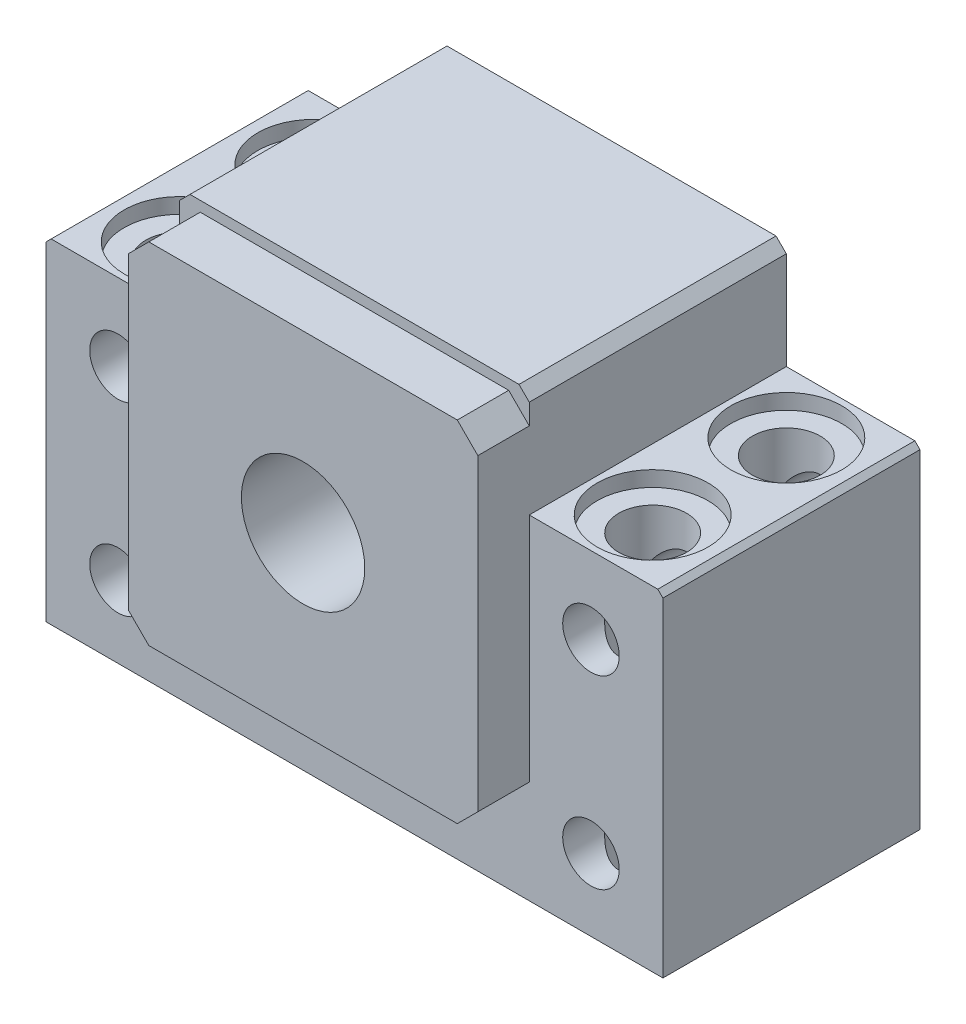
SolidWorks part; units mm, degrees
material "6061-T6 (SS)"
ref_plane "Спереди" through (0, 0, 0) normal (0, 0, 1) x (1, 0, 0)
ref_plane "Сверху" through (0, 0, 0) normal (0, 1, 0) x (1, 0, 0)
ref_plane "Справа" through (0, 0, 0) normal (1, 0, 0) x (0, 0, -1)
sketch "Эскиз1" plane through (0, 0, 0) normal (0, 0, 1) x (1, 0, 0)
  line L0 (0, -25) -> (0, 14) construction
  line L1 (-30, 7) -> (-30, -25)
  line L2 (-30, -25) -> (30, -25)
  line L3 (30, -25) -> (30, 7)
  line L4 (29.5, 7.5) -> (17, 7.5)
  line L5 (17, 7.5) -> (17, 17)
  line L6 (-17, 7.5) -> (-17, 17)
  line L7 (-29.5, 7.5) -> (-30, 7)
  line L8 (-29.5, 7.5) -> (-17, 7.5)
  line L9 (-23, -2.75) -> (-23, 2.75) construction
  line L10 (-16, 18) -> (16, 18)
  line L11 (23, -15.25) -> (23, -20.75) construction
  line L12 (-20.25, -18) -> (-25.75, -18) construction
  line L13 (20.25, -18) -> (25.75, -18) construction
  line L14 (-23, -15.25) -> (-23, -20.75) construction
  line L15 (23, -2.75) -> (23, 2.75) construction
  line L16 (30, 7) -> (29.5, 7.5)
  line L17 (-30, 0) -> (30, 0) construction
  line L18 (-17, 17) -> (-16, 18)
  line L19 (17, 17) -> (16, 18)
  circle A0 centre (0, 0) radius 6
  circle A1 centre (-23, 0) radius 2.75
  circle A2 centre (-23, -18) radius 2.75
  circle A3 centre (23, -18) radius 2.75
  circle A4 centre (23, 0) radius 2.75
  point P6 (30, 7.5)
  point P8 (17, 18)
  point P13 (-17, 18)
  point P16 (-30, 7.5)
  dimension "D1" = 60
  dimension "D9" = 5.5
  dimension "D2" = 46
  dimension "D3" = 30
  dimension "D4" = 25
  dimension "D5" = 32.5
  dimension "D6" = 43
  dimension "D7" = 34
  dimension "D8" = 18
extrude "Бобышка-Вытянуть1" add sketch "Эскиз1" against normal blind 25
sketch "Эскиз2" plane through (0, 0, 0) normal (0, 0, 1) x (1, 0, 0)
  line L0 (-17, 15) -> (-15, 17)
  line L1 (-15, 17) -> (15, 17)
  line L4 (17, 15) -> (17, -15)
  line L5 (15, -17) -> (-15, -17)
  line L6 (-17, -15) -> (-17, 15)
  line L7 (15, 17) -> (17, 15)
  line L8 (-15, -17) -> (-17, -15)
  line L9 (17, -15) -> (15, -17)
  circle A0 centre (0, 0) radius 6
  point P4 (-17, 17)
  point P6 (17, 17)
  point P11 (-17, -17)
  point P12 (17, -17)
extrude "Бобышка-Вытянуть2" add sketch "Эскиз2" along normal blind 5
sketch "Эскиз3" plane through (0, 0, 0) normal (0, 1, 0) x (1, 0, 0)
  line L0 (23, 25) -> (23, 0) construction
  line L1 (0, 25) -> (0, -5) construction
  line L4 (-30, 19) -> (30, 19) construction
  line L8 (-30, 6) -> (30, 6) construction
  line L10 (-23, 25) -> (-23, 0) construction
  circle A0 centre (-23, 19) radius 3.3
  circle A1 centre (-23, 6) radius 3.3
  circle A2 centre (23, 6) radius 3.3
  circle A3 centre (23, 19) radius 3.3
extrude "Вырез-Вытянуть1" cut sketch "Эскиз3" against normal through all from offset 7.5
sketch "Эскиз4" plane through (0, 0, 0) normal (0, 1, 0) x (1, 0, 0)
  circle A0 centre (-23, 19) radius 5.4
  circle A1 centre (-23, 6) radius 5.4
  circle A2 centre (23, 6) radius 5.4
  circle A3 centre (23, 19) radius 5.4
extrude "Вырез-Вытянуть2" cut sketch "Эскиз4" against normal blind 1.5 from offset 7.5
